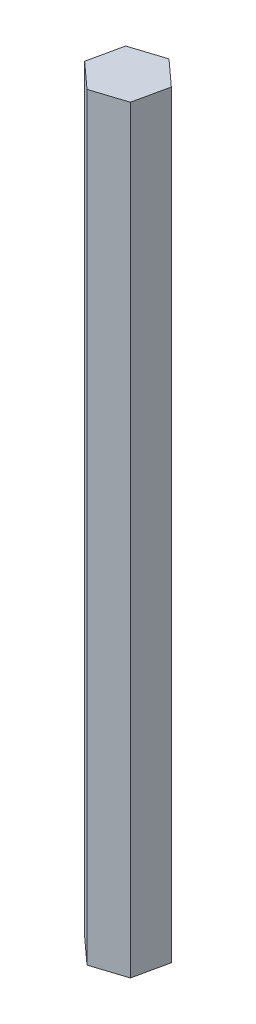
SolidWorks part; units mm, degrees
ref_plane "Front Plane" through (0, 0, 0) normal (0, 0, 1) x (1, 0, 0)
ref_plane "Top Plane" through (0, 0, 0) normal (0, 1, 0) x (1, 0, 0)
ref_plane "Right Plane" through (0, 0, 0) normal (1, 0, 0) x (0, 0, -1)
sketch "Sketch2" plane through (0, 0, 0) normal (0, 1, 0) x (1, 0, 0)
  line L1 (2.1373, -1.9404) -> (2.7491, 0.8807)
  line L2 (2.7491, 0.8807) -> (0.6118, 2.8212)
  line L3 (0.6118, 2.8212) -> (-2.1373, 1.9404)
  line L4 (-2.1373, 1.9404) -> (-2.7491, -0.8807)
  line L5 (-2.7491, -0.8807) -> (-0.6118, -2.8212)
  line L6 (-0.6118, -2.8212) -> (2.1373, -1.9404)
  circle A0 centre (0, 0) radius 2.5 construction
extrude "Boss-Extrude1" add sketch "Sketch2" along normal blind 63.5
